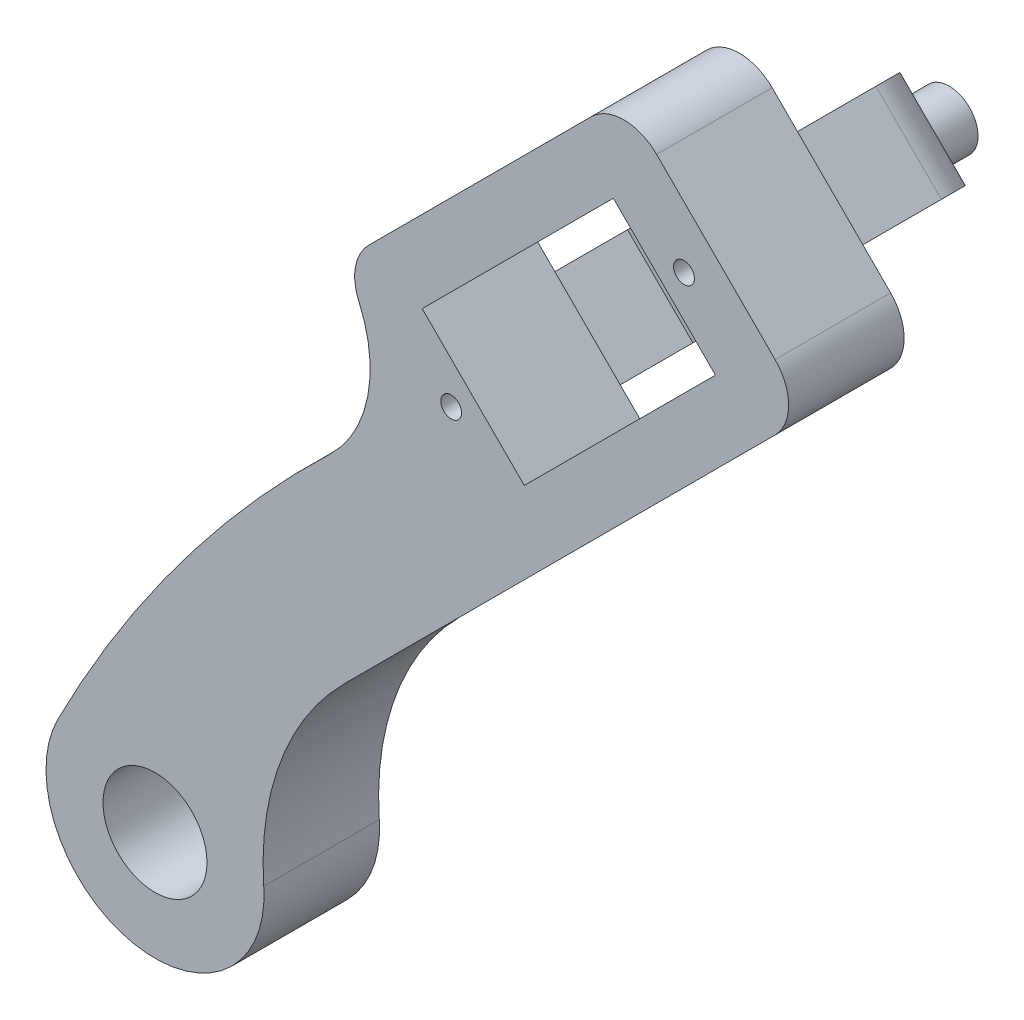
SolidWorks part; units mm, degrees
ref_plane "前视基准面" through (0, 0, 0) normal (0, 0, 1) x (1, 0, 0)
ref_plane "上视基准面" through (0, 0, 0) normal (0, 1, 0) x (1, 0, 0)
ref_plane "右视基准面" through (0, 0, 0) normal (1, 0, 0) x (0, 0, -1)
sketch "草图2" plane through (0, 0, 0) normal (0, 0, 1) x (1, 0, 0)
  line L0 (39.2294, 23.5816) -> (22.6831, 7.0353)
  line L1 (39.2294, 23.5816) -> (30.3905, 32.4204)
  line L2 (22.6831, 7.0353) -> (13.8442, 15.8741)
  line L3 (30.3905, 32.4204) -> (13.8442, 15.8741)
  line L4 (0, 0) -> (49.6838, 0) construction
  line L5 (0, 0) -> (0, -28.803) construction
  line L6 (7.1022, -15.6167) -> (44.3912, 21.6724)
  line L7 (44.3912, 27.3292) -> (34.1382, 37.5823)
  line L8 (28.4813, 37.5823) -> (9.2154, 18.3163)
  arc A0 (9.2154, 18.3163) -> (8.3621, 13.6812) centre (12.1521, 15.3796) ccw
  arc A1 (8.3621, 13.6812) -> (5.8862, 1.001) centre (-1.8675, 9.0968) cw
  arc A2 (-17.6852, -30.6634) -> (0.1294, -34.2938) centre (-9.2839, -34.9612) ccw
  arc A3 (0.1294, -34.2938) -> (7.1022, -15.6167) centre (24.0811, -32.5956) cw
  arc A4 (5.8862, 1.001) -> (-17.6852, -30.6634) centre (87.9841, -84.7194) ccw
  circle A5 centre (-9.2839, -34.9612) radius 4.5
  arc A6 (44.3912, 21.6724) -> (44.3912, 27.3292) centre (41.5628, 24.5008) ccw
  arc A7 (34.1382, 37.5823) -> (28.4813, 37.5823) centre (31.3098, 34.7539) ccw
  dimension "D7" = 82
  dimension "D8" = 9
  dimension "D9" = 4
  dimension "D1" = 12.5
  dimension "D2" = 23.4
  dimension "D3" = 5
  dimension "D4" = 6.3
  dimension "D5" = 5
  dimension "D6" = 45
extrude "凸台-拉伸1" add sketch "草图2" along normal blind 10
ref_plane "基准面1" through (3.2984, -3.2984, 0) normal (0.7071, -0.7071, 0) x (0, 0, -1)
sketch "草图4" plane through (3.2984, -3.2984, 0) normal (0.7071, -0.7071, 0) x (0, 0, -1)
  line L0 (0, 46.014) -> (7, 46.014)
  line L1 (7, 46.014) -> (7, 20.014)
  line L2 (7, 20.014) -> (0, 20.014)
  line L3 (0, 45.014) -> (0, 21.014)
  line L4 (0, -6.0207) -> (0, 46.714) construction
  line L5 (0, 49.014) -> (8, 49.014)
  line L7 (12, 45.014) -> (12, 21.014)
  line L8 (8, 17.014) -> (0, 17.014)
  line L9 (0, 46.714) -> (0, 50.714) construction
  line L10 (0, 45.014) -> (0, 49.014)
  line L11 (0, 21.014) -> (0, 17.014)
  arc A0 (12, 21.014) -> (8, 17.014) centre (8, 21.014) cw
  arc A1 (8, 49.014) -> (12, 45.014) centre (8, 45.014) cw
  point P14 (3.5, 46.014)
  dimension "D8" = 4
  dimension "D1" = 24
  dimension "D2" = 1
  dimension "D3" = 1
  dimension "D4" = 5
  dimension "D5" = 7
  dimension "D6" = 3
  dimension "D7" = 3
extrude "凸台-拉伸2" add sketch "草图4" along normal mid plane 8 contours A1 L5 L10 L0 L1 L2 L11 L8 A0 L7
sketch "草图5" plane through (0, 0, -12) normal (0, 0, -1) x (-1, 0, 0)
  line L4 (-15.3292, 14.3892) -> (-32.2997, 31.3598)
  line L5 (-32.2997, 31.3598) -> (-37.9566, 25.7029)
  line L6 (-37.9566, 25.7029) -> (-20.986, 8.7323)
  line L7 (-20.986, 8.7323) -> (-15.3292, 14.3892)
  line L8 (-15.3292, 14.3892) -> (-32.2997, 31.3598)
  line L9 (-32.2997, 31.3598) -> (-37.9566, 25.7029)
  line L10 (-37.9566, 25.7029) -> (-20.986, 8.7323)
  line L11 (-20.986, 8.7323) -> (-15.3292, 14.3892)
  circle A0 centre (-30.4612, 23.8644) radius 3
  point P6 (-35.1281, 28.5313)
  dimension "D4" = 6
  dimension "D2" = 4
  dimension "D3" = 6.6
  dimension "D1" = 0
extrude "凸台-拉伸3" add sketch "草图5" along normal blind 2 contours A0
sketch "草图6" plane through (0, 0, 10) normal (0, 0, 1) x (1, 0, 0)
  line L0 (13.8442, 15.8741) -> (22.6831, 7.0353) construction
  line L1 (39.2294, 23.5816) -> (30.3905, 32.4204) construction
  line L3 (7.1022, -15.6167) -> (44.3912, 21.6724)
  line L4 (44.3912, 27.3292) -> (34.1382, 37.5823)
  line L5 (28.4813, 37.5823) -> (9.2154, 18.3163)
  line L6 (7.1022, -15.6167) -> (44.3912, 21.6724)
  line L7 (44.3912, 27.3292) -> (34.1382, 37.5823)
  line L8 (28.4813, 37.5823) -> (9.2154, 18.3163)
  circle A0 centre (16.3545, 9.7576) radius 0.9
  circle A1 centre (36.507, 29.9102) radius 0.9
  arc A7 (7.1022, -15.6167) -> (0.1294, -34.2938) centre (24.0811, -32.5956) ccw
  arc A8 (44.3912, 21.6724) -> (44.3912, 27.3292) centre (41.5628, 24.5008) ccw
  arc A9 (34.1382, 37.5823) -> (28.4813, 37.5823) centre (31.3098, 34.7539) ccw
  arc A10 (9.2154, 18.3163) -> (8.3621, 13.6812) centre (12.1521, 15.3796) ccw
  arc A11 (5.8862, 1.001) -> (8.3621, 13.6812) centre (-1.8675, 9.0968) ccw
  arc A12 (5.8862, 1.001) -> (-17.6852, -30.6634) centre (87.9841, -84.7194) ccw
  arc A13 (-17.6852, -30.6634) -> (0.1294, -34.2938) centre (-9.2839, -34.9612) ccw
  arc A14 (7.1022, -15.6167) -> (0.1294, -34.2938) centre (24.0811, -32.5956) ccw
  arc A15 (44.3912, 21.6724) -> (44.3912, 27.3292) centre (41.5628, 24.5008) ccw
  arc A16 (34.1382, 37.5823) -> (28.4813, 37.5823) centre (31.3098, 34.7539) ccw
  arc A17 (9.2154, 18.3163) -> (8.3621, 13.6812) centre (12.1521, 15.3796) ccw
  arc A18 (5.8862, 1.001) -> (8.3621, 13.6812) centre (-1.8675, 9.0968) ccw
  arc A19 (5.8862, 1.001) -> (-17.6852, -30.6634) centre (87.9841, -84.7194) ccw
  arc A20 (-17.6852, -30.6634) -> (0.1294, -34.2938) centre (-9.2839, -34.9612) ccw
  dimension "D2" = 1.8
  dimension "D3" = 1.8
  dimension "D4" = 2.55
  dimension "D5" = 2.55
  dimension "D1" = 0
extrude "切除-拉伸1" cut sketch "草图6" against normal blind 8 contours A0 | A1
sketch "草图7" plane through (0, 0, -14) normal (0, 0, -1) x (-1, 0, 0)
  circle A0 centre (-30.4612, 23.8644) radius 2.5
extrude "凸台-拉伸4" add sketch "草图7" along normal blind 5
